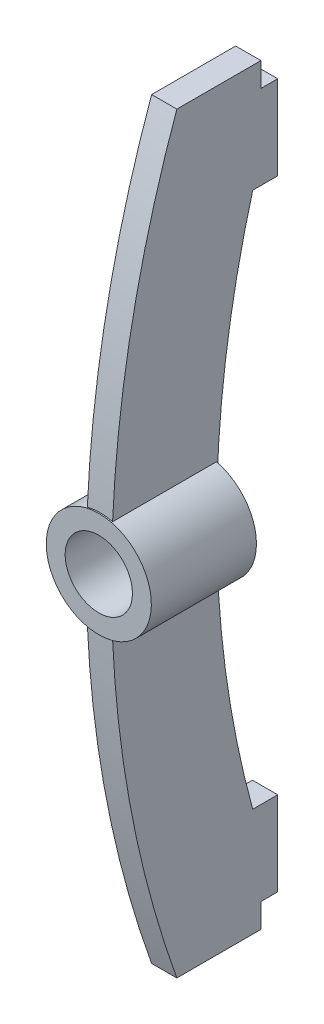
SolidWorks part; units mm, degrees
material "Plain Carbon Steel"
ref_plane "Front Plane" through (0, 0, 0) normal (0, 0, 1) x (1, 0, 0)
ref_plane "Top Plane" through (0, 0, 0) normal (0, 1, 0) x (1, 0, 0)
ref_plane "Right Plane" through (0, 0, 0) normal (1, 0, 0) x (0, 0, -1)
sketch "Sketch1" plane through (0, 0, 0) normal (1, 0, 0) x (0, 0, -1)
  line L0 (0, -167.5) -> (0, 167.5) construction
  line L1 (0, 167.5) -> (-8, 167.5)
  line L2 (-8, 167.5) -> (-8, 178.9887)
  line L3 (-48, 178.9887) -> (-8, 178.9887)
  line L4 (0, 0) -> (92.9085, 0) construction
  line L5 (-48, -178.9887) -> (-8, -178.9887)
  line L6 (-8, -167.5) -> (-8, -178.9887)
  line L7 (0, -167.5) -> (-8, -167.5)
  line L8 (0, 167.5) -> (0, 127.5)
  line L9 (0, -167.5) -> (0, -127.5)
  line L10 (0, 127.5) -> (-11.8896, 127.5)
  line L11 (0, -127.5) -> (-11.8896, -127.5)
  arc A0 (-48, 178.9887) -> (-48, -178.9887) centre (451.0879, 0) ccw
  arc A2 (-11.8896, 127.5) -> (-11.8896, -127.5) centre (451.0879, 0) ccw
  arc A4 (-0.9351, 162.1098) -> (-0.9351, -162.1098) centre (451.0879, 0) ccw construction
  point P4 (0, 0)
  dimension "D2" = 40
  dimension "D4" = 40
  dimension "D1" = 335
  dimension "D3" = 8
  dimension "D5" = 40
  dimension "D6" = 50
extrude "Boss-Extrude1" add sketch "Sketch1" along normal mid plane 12
sketch "Sketch2" plane through (0, 0, 0) normal (1, 0, 0) x (0, 0, -1)
  line L1 (-29.125, 0) -> (-79.125, 0)
  line L2 (-29.125, 0) -> (-29.125, 25)
  line L3 (-29.125, 25) -> (-79.125, 25)
  line L4 (-79.125, 0) -> (-79.125, 25)
  arc A0 (-11.8896, 127.5) -> (-11.8896, -127.5) centre (451.0879, 0) ccw construction
  arc A1 (-48, 178.9887) -> (-48, -178.9887) centre (451.0879, 0) ccw construction
  dimension "D1" = 25
revolve "Revolve1" add sketch "Sketch2" angle 360 about L1
sketch "Sketch3" plane through (0, 0, 0) normal (0, 0, 1) x (1, 0, 0)
  circle A0 centre (0, 0) radius 16
  dimension "D1" = 32
extrude "Cut-Extrude1" cut sketch "Sketch3" along normal through all
